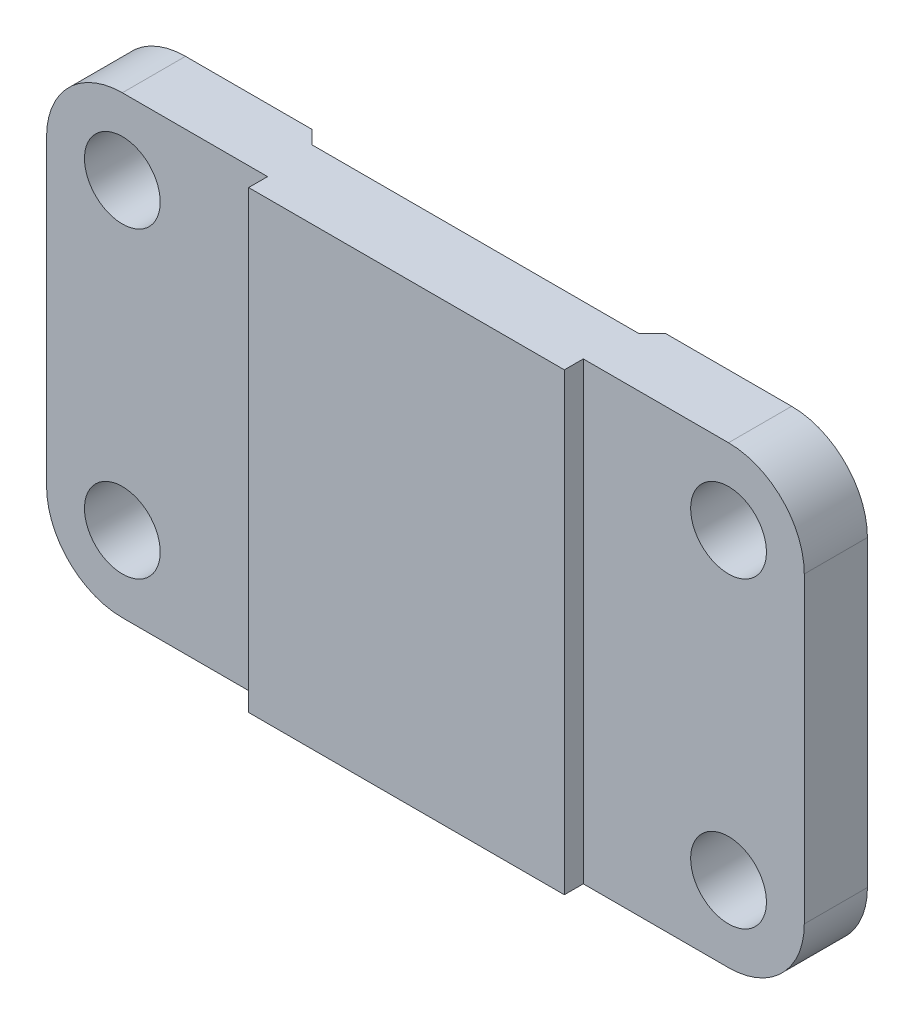
SolidWorks part; units mm, degrees
ref_plane "Front Plane" through (0, 0, 0) normal (0, 0, 1) x (1, 0, 0)
ref_plane "Top Plane" through (0, 0, 0) normal (0, 1, 0) x (1, 0, 0)
ref_plane "Right Plane" through (0, 0, 0) normal (1, 0, 0) x (0, 0, -1)
sketch "Sketch1" plane through (0, 0, 0) normal (0, 0, 1) x (1, 0, 0)
  line L1 (-48, 36) -> (48, 36)
  line L2 (-60, 24) -> (-60, -24)
  line L3 (-48, -36) -> (48, -36)
  line L4 (60, 24) -> (60, -24)
  line L5 (-60, 36) -> (60, -36) construction
  line L6 (-60, -36) -> (60, 36) construction
  arc A0 (-60, -24) -> (-48, -36) centre (-48, -24) ccw
  arc A1 (48, -36) -> (60, -24) centre (48, -24) ccw
  arc A2 (60, 24) -> (48, 36) centre (48, 24) ccw
  arc A3 (-48, 36) -> (-60, 24) centre (-48, 24) ccw
  point P0 (0, 0)
  dimension "D2" = 12
  dimension "D1" = 120
  dimension "72" = 72
extrude "Boss-Extrude1" add sketch "Sketch1" along normal blind 10
sketch "Sketch2" plane through (0, 0, 10) normal (0, 0, 1) x (1, 0, 0)
  line L2 (-48, -36) -> (48, -36) construction
  line L3 (0, 62.5734) -> (0, -64.2755) construction
  line L4 (60, -24) -> (60, 24) construction
  circle A0 centre (-48, 24) radius 6
  circle A2 centre (-48, -24) radius 6
  circle A3 centre (48, -24) radius 6
  circle A4 centre (48, 24) radius 6
  dimension "D1" = 48
  dimension "12" = 12
  dimension "D2" = 12
  dimension "D3" = 96
extrude "Cut-Extrude1" cut sketch "Sketch2" against normal through all
sketch "Sketch3" plane through (0, -36, 0) normal (0, -1, 0) x (1, 0, 0)
  line L0 (-28, 0) -> (28, 0)
  line L1 (-48, 0) -> (48, 0) construction
  line L2 (-28, 0) -> (-25.8787, 2.1213)
  line L3 (-25.8787, 2.1213) -> (25.8787, 2.1213)
  line L4 (25.8787, 2.1213) -> (28, 0)
  dimension "D1" = 56
  dimension "D2" = 45
  dimension "D3" = 28
  dimension "D4" = 3
  dimension "D5" = 45
extrude "Cut-Extrude2" cut sketch "Sketch3" against normal through all
sketch "Sketch4" plane through (0, 0, 10) normal (0, 0, 1) x (1, 0, 0)
  line L0 (-48, -36) -> (48, -36) construction
  line L1 (-25, 36) -> (25, 36)
  line L2 (-25, 36) -> (-25, -36)
  line L3 (-25, -36) -> (25, -36)
  line L4 (25, 36) -> (25, -36)
  line L5 (-25, 36) -> (25, -36) construction
  line L6 (-25, -36) -> (25, 36) construction
  point P0 (0, 0)
  dimension "D1" = 50
extrude "Boss-Extrude2" add sketch "Sketch4" along normal blind 3
